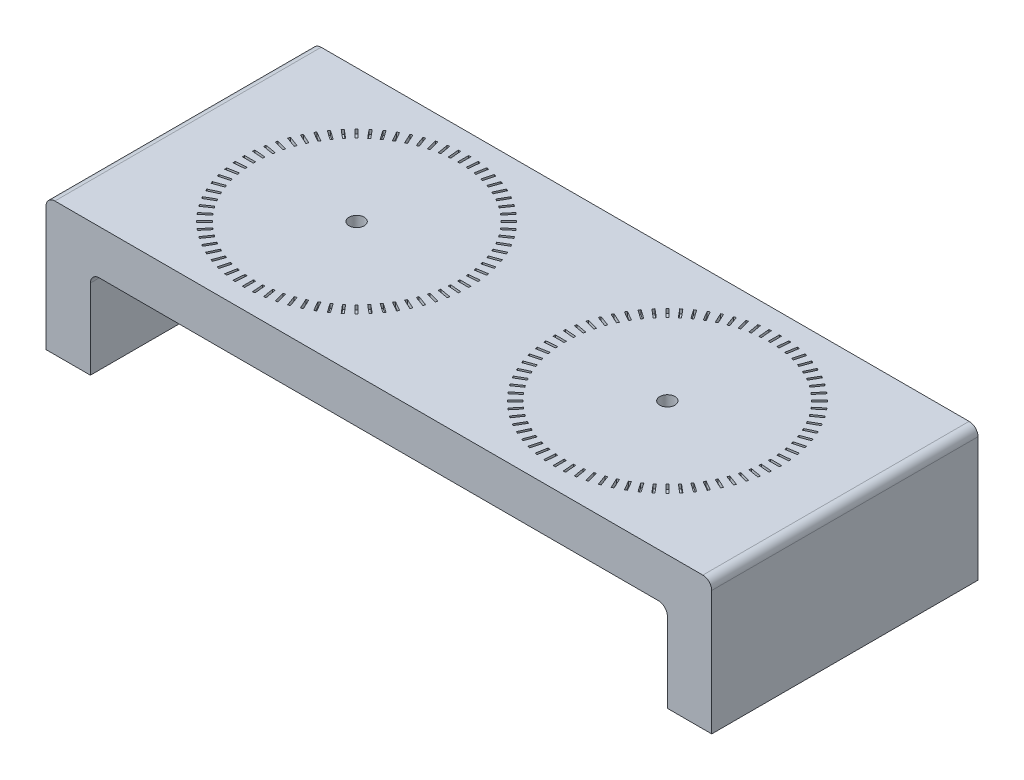
SolidWorks part; units mm, degrees
material "ABS"
ref_plane "Ön Düzlem" through (0, 0, 0) normal (0, 0, 1) x (1, 0, 0)
ref_plane "Üst Düzlem" through (0, 0, 0) normal (0, 1, 0) x (1, 0, 0)
ref_plane "Sağ Düzlem" through (0, 0, 0) normal (1, 0, 0) x (0, 0, -1)
sketch "Çizim1" plane through (0, 0, 0) normal (0, 1, 0) x (1, 0, 0)
  line L1 (-75, -30) -> (75, -30)
  line L2 (-75, -30) -> (-75, 30)
  line L3 (-75, 30) -> (75, 30)
  line L4 (75, -30) -> (75, 30)
  line L5 (-75, -30) -> (75, 30) construction
  line L6 (-75, 30) -> (75, -30) construction
  point P0 (0, 0)
  dimension "D1" = 150
  dimension "D2" = 60
extrude "Yükseklik-Ekstrüzyon1" add sketch "Çizim1" along normal blind 10
sketch "Çizim2" plane through (0, 10, 0) normal (0, 1, 0) x (1, 0, 0)
  line L0 (0, 0) -> (-35, 0) construction
  line L1 (-35, 17.5) -> (-35, 25)
  line L3 (-35.5, 25) -> (-34.5, 25)
  line L4 (-35.5, 25) -> (-35.5, 17.5)
  line L5 (-35.5, 17.5) -> (-34.5, 17.5)
  line L6 (-34.5, 25) -> (-34.5, 17.5)
  line L7 (-35.5, 25) -> (-34.5, 17.5) construction
  line L8 (-35.5, 17.5) -> (-34.5, 25) construction
  circle A0 centre (-35, 0) radius 17.5
  circle A1 centre (-35, 0) radius 25
  point P7 (-35, 21.25)
  dimension "D2" = 35
  dimension "D3" = 50
  dimension "D1" = 35
  dimension "D4" = 1
sketch "Çizim3" plane through (0, 10, 0) normal (0, 1, 0) x (1, 0, 0)
  circle A0 centre (-35, 0) radius 17.5
  dimension "D2" = 35
  dimension "D1" = 35
sketch "Çizim4" plane through (0, 10, 0) normal (0, 1, 0) x (1, 0, 0)
  line L0 (-33.0267, 25.4235) -> (-33.2444, 22.9355)
  line L1 (-35, 25.5) -> (-35, 23) construction
  line L2 (-35.25, 25.4988) -> (-34.75, 25.4988)
  line L3 (-35.25, 25.4988) -> (-35.25, 23.0012)
  line L4 (-35.25, 23.0012) -> (-34.75, 23.0012)
  line L5 (-34.75, 25.4988) -> (-34.75, 23.0012)
  line L6 (-35.25, 25.4988) -> (-34.75, 23.0012) construction
  line L7 (-35.25, 23.0012) -> (-34.75, 25.4988) construction
  line L8 (-33.0267, 25.4235) -> (-32.5286, 25.38)
  line L9 (-32.5286, 25.38) -> (-32.7463, 22.8919)
  line L10 (-33.2444, 22.9355) -> (-32.7463, 22.8919)
  line L11 (-30.8184, 25.1548) -> (-31.2521, 22.6952)
  line L12 (-30.8184, 25.1548) -> (-30.326, 25.068)
  line L13 (-30.326, 25.068) -> (-30.7597, 22.6084)
  line L14 (-31.2521, 22.6952) -> (-30.7597, 22.6084)
  line L15 (-28.6419, 24.6946) -> (-29.2883, 22.2822)
  line L16 (-28.6419, 24.6946) -> (-28.159, 24.5652)
  line L17 (-28.159, 24.5652) -> (-28.8054, 22.1528)
  line L18 (-29.2883, 22.2822) -> (-28.8054, 22.1528)
  line L19 (-26.5138, 24.0465) -> (-27.368, 21.6996)
  line L20 (-26.5138, 24.0465) -> (-26.044, 23.8755)
  line L21 (-26.044, 23.8755) -> (-26.8982, 21.5286)
  line L22 (-27.368, 21.6996) -> (-26.8982, 21.5286)
  line L23 (-24.4503, 23.2154) -> (-25.5058, 20.9518)
  line L24 (-24.4503, 23.2154) -> (-23.9972, 23.0041)
  line L25 (-23.9972, 23.0041) -> (-25.0527, 20.7405)
  line L26 (-25.5058, 20.9518) -> (-25.0527, 20.7405)
  line L27 (-22.4671, 22.2076) -> (-23.7159, 20.0446)
  line L28 (-22.4671, 22.2076) -> (-22.0341, 21.9576)
  line L29 (-22.0341, 21.9576) -> (-23.2829, 19.7946)
  line L30 (-23.7159, 20.0446) -> (-23.2829, 19.7946)
  line L31 (-20.5793, 21.0308) -> (-22.0118, 18.9849)
  line L32 (-20.5793, 21.0308) -> (-20.1697, 20.744)
  line L33 (-20.1697, 20.744) -> (-21.6023, 18.6981)
  line L34 (-22.0118, 18.9849) -> (-21.6023, 18.6981)
  line L35 (-18.8012, 19.6939) -> (-20.4066, 17.7807)
  line L36 (-18.8012, 19.6939) -> (-18.4182, 19.3725)
  line L37 (-18.4182, 19.3725) -> (-20.0236, 17.4593)
  line L38 (-20.4066, 17.7807) -> (-20.0236, 17.4593)
  line L39 (-17.1464, 18.2071) -> (-18.9125, 16.4411)
  line L40 (-17.1464, 18.2071) -> (-16.7929, 17.8536)
  line L41 (-16.7929, 17.8536) -> (-18.5589, 16.0875)
  line L42 (-18.9125, 16.4411) -> (-18.5589, 16.0875)
  line L43 (-15.6275, 16.5818) -> (-17.5407, 14.9764)
  line L44 (-15.6275, 16.5818) -> (-15.3061, 16.1988)
  line L45 (-15.3061, 16.1988) -> (-17.2193, 14.5934)
  line L46 (-17.5407, 14.9764) -> (-17.2193, 14.5934)
  line L47 (-14.256, 14.8303) -> (-16.3019, 13.3977)
  line L48 (-14.256, 14.8303) -> (-13.9692, 14.4207)
  line L49 (-13.9692, 14.4207) -> (-16.0151, 12.9882)
  line L50 (-16.3019, 13.3977) -> (-16.0151, 12.9882)
  line L51 (-13.0424, 12.9659) -> (-15.2054, 11.7171)
  line L52 (-13.0424, 12.9659) -> (-12.7924, 12.5329)
  line L53 (-12.7924, 12.5329) -> (-14.9554, 11.2841)
  line L54 (-15.2054, 11.7171) -> (-14.9554, 11.2841)
  line L55 (-11.9959, 11.0028) -> (-14.2595, 9.9473)
  line L56 (-11.9959, 11.0028) -> (-11.7846, 10.5497)
  line L57 (-11.7846, 10.5497) -> (-14.0482, 9.4942)
  line L58 (-14.2595, 9.9473) -> (-14.0482, 9.4942)
  line L59 (-11.1245, 8.956) -> (-13.4714, 8.1018)
  line L60 (-11.1245, 8.956) -> (-10.9535, 8.4862)
  line L61 (-10.9535, 8.4862) -> (-13.3004, 7.632)
  line L62 (-13.4714, 8.1018) -> (-13.3004, 7.632)
  line L63 (-10.4348, 6.841) -> (-12.8472, 6.1946)
  line L64 (-10.4348, 6.841) -> (-10.3054, 6.3581)
  line L65 (-10.3054, 6.3581) -> (-12.7178, 5.7117)
  line L66 (-12.8472, 6.1946) -> (-12.7178, 5.7117)
  line L67 (-9.932, 4.674) -> (-12.3916, 4.2403)
  line L68 (-9.932, 4.674) -> (-9.8452, 4.1816)
  line L69 (-9.8452, 4.1816) -> (-12.3048, 3.7479)
  line L70 (-12.3916, 4.2403) -> (-12.3048, 3.7479)
  line L71 (-9.62, 2.4714) -> (-12.1081, 2.2537)
  line L72 (-9.62, 2.4714) -> (-9.5765, 1.9733)
  line L73 (-9.5765, 1.9733) -> (-12.0645, 1.7556)
  line L74 (-12.1081, 2.2537) -> (-12.0645, 1.7556)
  line L75 (-9.5012, 0.25) -> (-11.9988, 0.25)
  line L76 (-9.5012, 0.25) -> (-9.5012, -0.25)
  line L77 (-9.5012, -0.25) -> (-11.9988, -0.25)
  line L78 (-11.9988, 0.25) -> (-11.9988, -0.25)
  line L79 (-9.5765, -1.9733) -> (-12.0645, -1.7556)
  line L80 (-9.5765, -1.9733) -> (-9.62, -2.4714)
  line L81 (-9.62, -2.4714) -> (-12.1081, -2.2537)
  line L82 (-12.0645, -1.7556) -> (-12.1081, -2.2537)
  line L83 (-9.8452, -4.1816) -> (-12.3048, -3.7479)
  line L84 (-9.8452, -4.1816) -> (-9.932, -4.674)
  line L85 (-9.932, -4.674) -> (-12.3916, -4.2403)
  line L86 (-12.3048, -3.7479) -> (-12.3916, -4.2403)
  line L87 (-10.3054, -6.3581) -> (-12.7178, -5.7117)
  line L88 (-10.3054, -6.3581) -> (-10.4348, -6.841)
  line L89 (-10.4348, -6.841) -> (-12.8472, -6.1946)
  line L90 (-12.7178, -5.7117) -> (-12.8472, -6.1946)
  line L91 (-10.9535, -8.4862) -> (-13.3004, -7.632)
  line L92 (-10.9535, -8.4862) -> (-11.1245, -8.956)
  line L93 (-11.1245, -8.956) -> (-13.4714, -8.1018)
  line L94 (-13.3004, -7.632) -> (-13.4714, -8.1018)
  line L95 (-11.7846, -10.5497) -> (-14.0482, -9.4942)
  line L96 (-11.7846, -10.5497) -> (-11.9959, -11.0028)
  line L97 (-11.9959, -11.0028) -> (-14.2595, -9.9473)
  line L98 (-14.0482, -9.4942) -> (-14.2595, -9.9473)
  line L99 (-12.7924, -12.5329) -> (-14.9554, -11.2841)
  line L100 (-12.7924, -12.5329) -> (-13.0424, -12.9659)
  line L101 (-13.0424, -12.9659) -> (-15.2054, -11.7171)
  line L102 (-14.9554, -11.2841) -> (-15.2054, -11.7171)
  line L103 (-13.9692, -14.4207) -> (-16.0151, -12.9882)
  line L104 (-13.9692, -14.4207) -> (-14.256, -14.8303)
  line L105 (-14.256, -14.8303) -> (-16.3019, -13.3977)
  line L106 (-16.0151, -12.9882) -> (-16.3019, -13.3977)
  line L107 (-15.3061, -16.1988) -> (-17.2193, -14.5934)
  line L108 (-15.3061, -16.1988) -> (-15.6275, -16.5818)
  line L109 (-15.6275, -16.5818) -> (-17.5407, -14.9764)
  line L110 (-17.2193, -14.5934) -> (-17.5407, -14.9764)
  line L111 (-16.7929, -17.8536) -> (-18.5589, -16.0875)
  line L112 (-16.7929, -17.8536) -> (-17.1464, -18.2071)
  line L113 (-17.1464, -18.2071) -> (-18.9125, -16.4411)
  line L114 (-18.5589, -16.0875) -> (-18.9125, -16.4411)
  line L115 (-18.4182, -19.3725) -> (-20.0236, -17.4593)
  line L116 (-18.4182, -19.3725) -> (-18.8012, -19.6939)
  line L117 (-18.8012, -19.6939) -> (-20.4066, -17.7807)
  line L118 (-20.0236, -17.4593) -> (-20.4066, -17.7807)
  line L119 (-20.1697, -20.744) -> (-21.6023, -18.6981)
  line L120 (-20.1697, -20.744) -> (-20.5793, -21.0308)
  line L121 (-20.5793, -21.0308) -> (-22.0118, -18.9849)
  line L122 (-21.6023, -18.6981) -> (-22.0118, -18.9849)
  line L123 (-22.0341, -21.9576) -> (-23.2829, -19.7946)
  line L124 (-22.0341, -21.9576) -> (-22.4671, -22.2076)
  line L125 (-22.4671, -22.2076) -> (-23.7159, -20.0446)
  line L126 (-23.2829, -19.7946) -> (-23.7159, -20.0446)
  line L127 (-23.9972, -23.0041) -> (-25.0527, -20.7405)
  line L128 (-23.9972, -23.0041) -> (-24.4503, -23.2154)
  line L129 (-24.4503, -23.2154) -> (-25.5058, -20.9518)
  line L130 (-25.0527, -20.7405) -> (-25.5058, -20.9518)
  line L131 (-26.044, -23.8755) -> (-26.8982, -21.5286)
  line L132 (-26.044, -23.8755) -> (-26.5138, -24.0465)
  line L133 (-26.5138, -24.0465) -> (-27.368, -21.6996)
  line L134 (-26.8982, -21.5286) -> (-27.368, -21.6996)
  line L135 (-28.159, -24.5652) -> (-28.8054, -22.1528)
  line L136 (-28.159, -24.5652) -> (-28.6419, -24.6946)
  line L137 (-28.6419, -24.6946) -> (-29.2883, -22.2822)
  line L138 (-28.8054, -22.1528) -> (-29.2883, -22.2822)
  line L139 (-30.326, -25.068) -> (-30.7597, -22.6084)
  line L140 (-30.326, -25.068) -> (-30.8184, -25.1548)
  line L141 (-30.8184, -25.1548) -> (-31.2521, -22.6952)
  line L142 (-30.7597, -22.6084) -> (-31.2521, -22.6952)
  line L143 (-32.5286, -25.38) -> (-32.7463, -22.8919)
  line L144 (-32.5286, -25.38) -> (-33.0267, -25.4235)
  line L145 (-33.0267, -25.4235) -> (-33.2444, -22.9355)
  line L146 (-32.7463, -22.8919) -> (-33.2444, -22.9355)
  line L147 (-34.75, -25.4988) -> (-34.75, -23.0012)
  line L148 (-34.75, -25.4988) -> (-35.25, -25.4988)
  line L149 (-35.25, -25.4988) -> (-35.25, -23.0012)
  line L150 (-34.75, -23.0012) -> (-35.25, -23.0012)
  line L151 (-36.9733, -25.4235) -> (-36.7556, -22.9355)
  line L152 (-36.9733, -25.4235) -> (-37.4714, -25.38)
  line L153 (-37.4714, -25.38) -> (-37.2537, -22.8919)
  line L154 (-36.7556, -22.9355) -> (-37.2537, -22.8919)
  line L155 (-39.1816, -25.1548) -> (-38.7479, -22.6952)
  line L156 (-39.1816, -25.1548) -> (-39.674, -25.068)
  line L157 (-39.674, -25.068) -> (-39.2403, -22.6084)
  line L158 (-38.7479, -22.6952) -> (-39.2403, -22.6084)
  line L159 (-41.3581, -24.6946) -> (-40.7117, -22.2822)
  line L160 (-41.3581, -24.6946) -> (-41.841, -24.5652)
  line L161 (-41.841, -24.5652) -> (-41.1946, -22.1528)
  line L162 (-40.7117, -22.2822) -> (-41.1946, -22.1528)
  line L163 (-43.4862, -24.0465) -> (-42.632, -21.6996)
  line L164 (-43.4862, -24.0465) -> (-43.956, -23.8755)
  line L165 (-43.956, -23.8755) -> (-43.1018, -21.5286)
  line L166 (-42.632, -21.6996) -> (-43.1018, -21.5286)
  line L167 (-45.5497, -23.2154) -> (-44.4942, -20.9518)
  line L168 (-45.5497, -23.2154) -> (-46.0028, -23.0041)
  line L169 (-46.0028, -23.0041) -> (-44.9473, -20.7405)
  line L170 (-44.4942, -20.9518) -> (-44.9473, -20.7405)
  line L171 (-47.5329, -22.2076) -> (-46.2841, -20.0446)
  line L172 (-47.5329, -22.2076) -> (-47.9659, -21.9576)
  line L173 (-47.9659, -21.9576) -> (-46.7171, -19.7946)
  line L174 (-46.2841, -20.0446) -> (-46.7171, -19.7946)
  line L175 (-49.4207, -21.0308) -> (-47.9882, -18.9849)
  line L176 (-49.4207, -21.0308) -> (-49.8303, -20.744)
  line L177 (-49.8303, -20.744) -> (-48.3977, -18.6981)
  line L178 (-47.9882, -18.9849) -> (-48.3977, -18.6981)
  line L179 (-51.1988, -19.6939) -> (-49.5934, -17.7807)
  line L180 (-51.1988, -19.6939) -> (-51.5818, -19.3725)
  line L181 (-51.5818, -19.3725) -> (-49.9764, -17.4593)
  line L182 (-49.5934, -17.7807) -> (-49.9764, -17.4593)
  line L183 (-52.8536, -18.2071) -> (-51.0875, -16.4411)
  line L184 (-52.8536, -18.2071) -> (-53.2071, -17.8536)
  line L185 (-53.2071, -17.8536) -> (-51.4411, -16.0875)
  line L186 (-51.0875, -16.4411) -> (-51.4411, -16.0875)
  line L187 (-54.3725, -16.5818) -> (-52.4593, -14.9764)
  line L188 (-54.3725, -16.5818) -> (-54.6939, -16.1988)
  line L189 (-54.6939, -16.1988) -> (-52.7807, -14.5934)
  line L190 (-52.4593, -14.9764) -> (-52.7807, -14.5934)
  line L191 (-55.744, -14.8303) -> (-53.6981, -13.3977)
  line L192 (-55.744, -14.8303) -> (-56.0308, -14.4207)
  line L193 (-56.0308, -14.4207) -> (-53.9849, -12.9882)
  line L194 (-53.6981, -13.3977) -> (-53.9849, -12.9882)
  line L195 (-56.9576, -12.9659) -> (-54.7946, -11.7171)
  line L196 (-56.9576, -12.9659) -> (-57.2076, -12.5329)
  line L197 (-57.2076, -12.5329) -> (-55.0446, -11.2841)
  line L198 (-54.7946, -11.7171) -> (-55.0446, -11.2841)
  line L199 (-58.0041, -11.0028) -> (-55.7405, -9.9473)
  line L200 (-58.0041, -11.0028) -> (-58.2154, -10.5497)
  line L201 (-58.2154, -10.5497) -> (-55.9518, -9.4942)
  line L202 (-55.7405, -9.9473) -> (-55.9518, -9.4942)
  line L203 (-58.8755, -8.956) -> (-56.5286, -8.1018)
  line L204 (-58.8755, -8.956) -> (-59.0465, -8.4862)
  line L205 (-59.0465, -8.4862) -> (-56.6996, -7.632)
  line L206 (-56.5286, -8.1018) -> (-56.6996, -7.632)
  line L207 (-59.5652, -6.841) -> (-57.1528, -6.1946)
  line L208 (-59.5652, -6.841) -> (-59.6946, -6.3581)
  line L209 (-59.6946, -6.3581) -> (-57.2822, -5.7117)
  line L210 (-57.1528, -6.1946) -> (-57.2822, -5.7117)
  line L211 (-60.068, -4.674) -> (-57.6084, -4.2403)
  line L212 (-60.068, -4.674) -> (-60.1548, -4.1816)
  line L213 (-60.1548, -4.1816) -> (-57.6952, -3.7479)
  line L214 (-57.6084, -4.2403) -> (-57.6952, -3.7479)
  line L215 (-60.38, -2.4714) -> (-57.8919, -2.2537)
  line L216 (-60.38, -2.4714) -> (-60.4235, -1.9733)
  line L217 (-60.4235, -1.9733) -> (-57.9355, -1.7556)
  line L218 (-57.8919, -2.2537) -> (-57.9355, -1.7556)
  line L219 (-60.4988, -0.25) -> (-58.0012, -0.25)
  line L220 (-60.4988, -0.25) -> (-60.4988, 0.25)
  line L221 (-60.4988, 0.25) -> (-58.0012, 0.25)
  line L222 (-58.0012, -0.25) -> (-58.0012, 0.25)
  line L223 (-60.4235, 1.9733) -> (-57.9355, 1.7556)
  line L224 (-60.4235, 1.9733) -> (-60.38, 2.4714)
  line L225 (-60.38, 2.4714) -> (-57.8919, 2.2537)
  line L226 (-57.9355, 1.7556) -> (-57.8919, 2.2537)
  line L227 (-60.1548, 4.1816) -> (-57.6952, 3.7479)
  line L228 (-60.1548, 4.1816) -> (-60.068, 4.674)
  line L229 (-60.068, 4.674) -> (-57.6084, 4.2403)
  line L230 (-57.6952, 3.7479) -> (-57.6084, 4.2403)
  line L231 (-59.6946, 6.3581) -> (-57.2822, 5.7117)
  line L232 (-59.6946, 6.3581) -> (-59.5652, 6.841)
  line L233 (-59.5652, 6.841) -> (-57.1528, 6.1946)
  line L234 (-57.2822, 5.7117) -> (-57.1528, 6.1946)
  line L235 (-59.0465, 8.4862) -> (-56.6996, 7.632)
  line L236 (-59.0465, 8.4862) -> (-58.8755, 8.956)
  line L237 (-58.8755, 8.956) -> (-56.5286, 8.1018)
  line L238 (-56.6996, 7.632) -> (-56.5286, 8.1018)
  line L239 (-58.2154, 10.5497) -> (-55.9518, 9.4942)
  line L240 (-58.2154, 10.5497) -> (-58.0041, 11.0028)
  line L241 (-58.0041, 11.0028) -> (-55.7405, 9.9473)
  line L242 (-55.9518, 9.4942) -> (-55.7405, 9.9473)
  line L243 (-57.2076, 12.5329) -> (-55.0446, 11.2841)
  line L244 (-57.2076, 12.5329) -> (-56.9576, 12.9659)
  line L245 (-56.9576, 12.9659) -> (-54.7946, 11.7171)
  line L246 (-55.0446, 11.2841) -> (-54.7946, 11.7171)
  line L247 (-56.0308, 14.4207) -> (-53.9849, 12.9882)
  line L248 (-56.0308, 14.4207) -> (-55.744, 14.8303)
  line L249 (-55.744, 14.8303) -> (-53.6981, 13.3977)
  line L250 (-53.9849, 12.9882) -> (-53.6981, 13.3977)
  line L251 (-54.6939, 16.1988) -> (-52.7807, 14.5934)
  line L252 (-54.6939, 16.1988) -> (-54.3725, 16.5818)
  line L253 (-54.3725, 16.5818) -> (-52.4593, 14.9764)
  line L254 (-52.7807, 14.5934) -> (-52.4593, 14.9764)
  line L255 (-53.2071, 17.8536) -> (-51.4411, 16.0875)
  line L256 (-53.2071, 17.8536) -> (-52.8536, 18.2071)
  line L257 (-52.8536, 18.2071) -> (-51.0875, 16.4411)
  line L258 (-51.4411, 16.0875) -> (-51.0875, 16.4411)
  line L259 (-51.5818, 19.3725) -> (-49.9764, 17.4593)
  line L260 (-51.5818, 19.3725) -> (-51.1988, 19.6939)
  line L261 (-51.1988, 19.6939) -> (-49.5934, 17.7807)
  line L262 (-49.9764, 17.4593) -> (-49.5934, 17.7807)
  line L263 (-49.8303, 20.744) -> (-48.3977, 18.6981)
  line L264 (-49.8303, 20.744) -> (-49.4207, 21.0308)
  line L265 (-49.4207, 21.0308) -> (-47.9882, 18.9849)
  line L266 (-48.3977, 18.6981) -> (-47.9882, 18.9849)
  line L267 (-47.9659, 21.9576) -> (-46.7171, 19.7946)
  line L268 (-47.9659, 21.9576) -> (-47.5329, 22.2076)
  line L269 (-47.5329, 22.2076) -> (-46.2841, 20.0446)
  line L270 (-46.7171, 19.7946) -> (-46.2841, 20.0446)
  line L271 (-46.0028, 23.0041) -> (-44.9473, 20.7405)
  line L272 (-46.0028, 23.0041) -> (-45.5497, 23.2154)
  line L273 (-45.5497, 23.2154) -> (-44.4942, 20.9518)
  line L274 (-44.9473, 20.7405) -> (-44.4942, 20.9518)
  line L275 (-43.956, 23.8755) -> (-43.1018, 21.5286)
  line L276 (-43.956, 23.8755) -> (-43.4862, 24.0465)
  line L277 (-43.4862, 24.0465) -> (-42.632, 21.6996)
  line L278 (-43.1018, 21.5286) -> (-42.632, 21.6996)
  line L279 (-41.841, 24.5652) -> (-41.1946, 22.1528)
  line L280 (-41.841, 24.5652) -> (-41.3581, 24.6946)
  line L281 (-41.3581, 24.6946) -> (-40.7117, 22.2822)
  line L282 (-41.1946, 22.1528) -> (-40.7117, 22.2822)
  line L283 (-39.674, 25.068) -> (-39.2403, 22.6084)
  line L284 (-39.674, 25.068) -> (-39.1816, 25.1548)
  line L285 (-39.1816, 25.1548) -> (-38.7479, 22.6952)
  line L286 (-39.2403, 22.6084) -> (-38.7479, 22.6952)
  line L287 (-37.4714, 25.38) -> (-37.2537, 22.8919)
  line L288 (-37.4714, 25.38) -> (-36.9733, 25.4235)
  line L289 (-36.9733, 25.4235) -> (-36.7556, 22.9355)
  line L290 (-37.2537, 22.8919) -> (-36.7556, 22.9355)
  circle A0 centre (-35, 0) radius 25.5
  circle A1 centre (-35, 0) radius 23
  point P4 (-35, 24.25)
  point P299 (-35, 0)
  dimension "51" = 51
  dimension "D2" = 46
  dimension "D3" = 0.5
  dimension "D4" = 72
extrude "Kes-Ekstrüzyon1" cut sketch "Çizim4" against normal blind 1 contours L0 L10 L9 L8 | L5 L2 L3 L4 | L287 L290 L289 L288 | L279 L282 L281 L280 | L283 L286 L285 L284 | L275 L278 L277 L276 | L271 L274 L273 L272 | L267 L270 L269 L268 | L263 L266 L265 L264 | L259 L262 L261 L260 | L255 L258 L257 L256 | L251 L254 L253 L252 | L247 L250 L249 L248 | L243 L246 L245 L244 | L239 L242 L241 L240 | L235 L238 L237 L236 | L231 L234 L233 L232 | L227 L230 L229 L228 | L223 L226 L225 L224 | L219 L222 L221 L220 | L215 L218 L217 L216 | L211 L214 L213 L212 | L207 L210 L209 L208 | L203 L206 L205 L204 | L199 L202 L201 L200 | L195 L198 L197 L196 | L191 L194 L193 L192 | L187 L190 L189 L188 | L183 L186 L185 L184 | L179 L182 L181 L180 | L175 L178 L177 L176 | L171 L174 L173 L172 | L167 L170 L169 L168 | L163 L166 L165 L164 | L159 L162 L161 L160 | L155 L158 L157 L156 | L151 L154 L153 L152 | L147 L150 L149 L148 | L143 L146 L145 L144 | L139 L142 L141 L140 | L131 L134 L133 L132 | L123 L126 L125 L124 | L119 L122 L121 L120 | L115 L118 L117 L116 | L111 L114 L113 L112 | L107 L110 L109 L108 | L103 L106 L105 L104 | L99 L102 L101 L100 | L95 L98 L97 L96 | L91 L94 L93 L92 | L87 L90 L89 L88 | L79 L82 L81 L80 | L75 L78 L77 L76 | L71 L74 L73 L72 | L67 L70 L69 L68 | L63 L66 L65 L64 | L59 L62 L61 L60 | L55 L58 L57 L56 | L51 L54 L53 L52 | L47 L50 L49 L48 | L43 L46 L45 L44 | L11 L14 L13 L12 | L15 L18 L17 L16 | L19 L22 L21 L20 | L23 L26 L25 L24 | L27 L30 L29 L28 | L31 L34 L33 L32 | L35 L38 L37 L36 | L39 L42 L41 L40 | L135 L138 L137 L136 | L127 L130 L129 L128 | L83 L86 L85 L84
mirror "Aynalama1" about plane through (0, 0, 0) normal (1, 0, 0) of "Kes-Ekstrüzyon1"
hole_wizard "M3 Mercimek Başlı Vida İçin Havşa1" positions "Çizim5" profile "Çizim6" counterbore size "M3" standard "ISO" end condition through all
sketch "Çizim5" plane through (0, 0, 0) normal (0, -1, 0) x (-1, 0, 0)
  point P0 (35, 0)
sketch "Çizim6" plane through (-35, 0, 0) normal (1, 0, 0) x (0, 0, -1)
  line L0 (0, 0) -> (0, 10)
  line L1 (0, 10) -> (1.7, 10)
  line L3 (1.7, 10) -> (1.7, 3)
  line L4 (3.25, 3) -> (1.7, 3)
  line L5 (3.25, 3) -> (3.25, 0.025)
  line L6 (3.25, 0.025) -> (3.275, 0)
  line L7 (3.275, 0) -> (0, 0)
  line L8 (-3.25, 0.025) -> (-3.275, 0) construction
  line L11 (0, -6.35) -> (0, 107.95) construction
  dimension "Thru Hole Dia." = 3.4
  dimension "Thru Hole Depth" = 10
  dimension "C'Bore Dia." = 6.5
  dimension "C'Bore Depth" = 3
  dimension "Near C'Sink Dia." = 6.55
  dimension "Near C'Sink Angle" = 90
mirror "Aynalama2" about plane through (0, 0, 0) normal (1, 0, 0) of "M3 Mercimek Başlı Vida İçin Havşa1"
sketch "Çizim7" plane through (0, 0, 0) normal (0, -1, 0) x (1, 0, 0)
  line L0 (75, -30) -> (-75, -30) construction
  line L1 (-75, 30) -> (-65, 30)
  line L2 (-75, 30) -> (-75, -30)
  line L3 (-75, -30) -> (-65, -30)
  line L4 (-65, 30) -> (-65, -30)
  line L6 (75, 30) -> (65, 30)
  line L7 (75, 30) -> (75, -30)
  line L8 (75, -30) -> (65, -30)
  line L9 (65, 30) -> (65, -30)
  dimension "D1" = 10
  dimension "D2" = 10
extrude "Yükseklik-Ekstrüzyon3" add sketch "Çizim7" along normal blind 20 contours L2 L1 L4 L3 | L7 L6 L9 L8
fillet "Radyus1" radius 2 4 edges at (75, 10, 0) (-75, 10, 0) (-65, 0, 0) (65, 0, 0)
